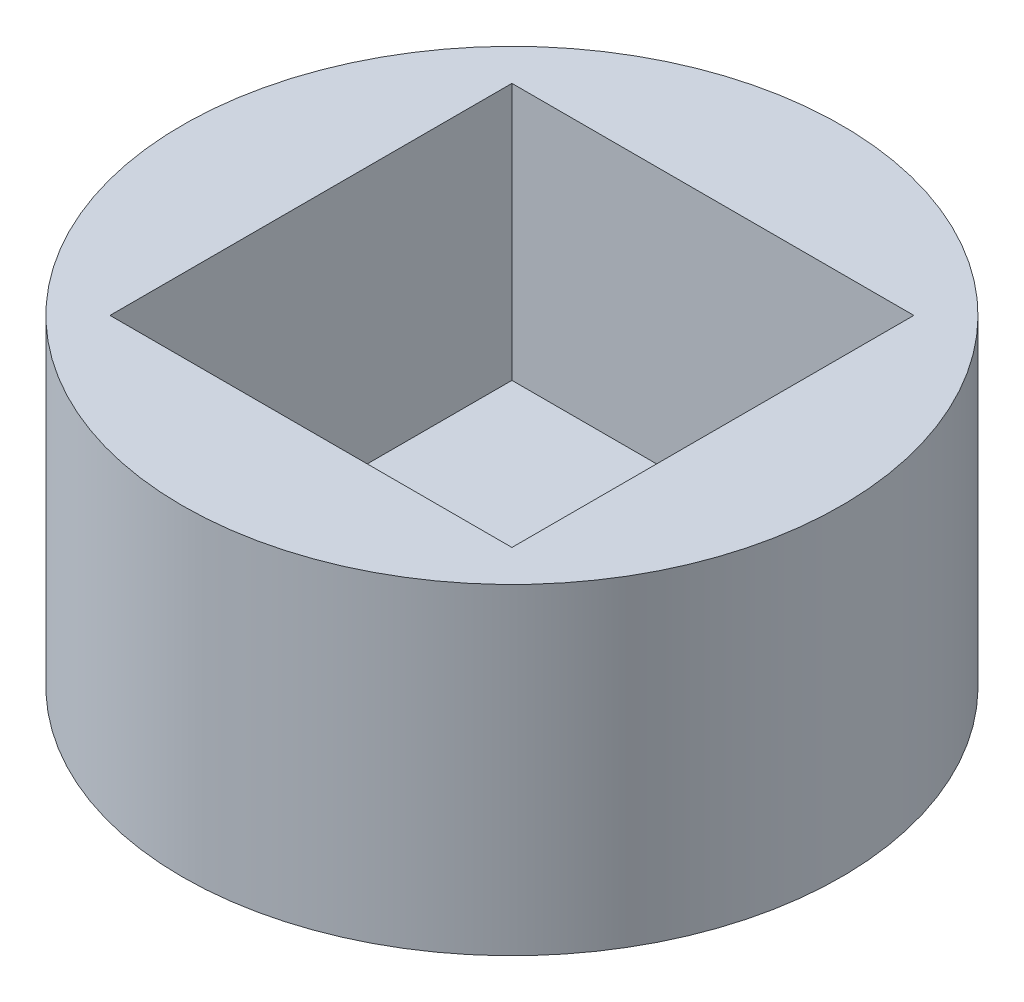
SolidWorks part; units mm, degrees
ref_plane "Front Plane" through (0, 0, 0) normal (0, 0, 1) x (1, 0, 0)
ref_plane "Top Plane" through (0, 0, 0) normal (0, 1, 0) x (1, 0, 0)
ref_plane "Right Plane" through (0, 0, 0) normal (1, 0, 0) x (0, 0, -1)
sketch "Sketch1" plane through (0, 0, 0) normal (0, 1, 0) x (1, 0, 0)
  circle A0 centre (0, 0) radius 26.035
  dimension "D1" = 52.07
extrude "Boss-Extrude1" add sketch "Sketch1" along normal blind 25.4
sketch "Sketch2" plane through (0, 25.4, 0) normal (0, 1, 0) x (1, 0, 0)
  line L1 (-15.875, -15.875) -> (15.875, -15.875)
  line L2 (-15.875, -15.875) -> (-15.875, 15.875)
  line L3 (-15.875, 15.875) -> (15.875, 15.875)
  line L4 (15.875, -15.875) -> (15.875, 15.875)
  line L5 (-15.875, -15.875) -> (15.875, 15.875) construction
  line L6 (-15.875, 15.875) -> (15.875, -15.875) construction
  point P0 (0, 0)
  dimension "D1" = 31.75
  dimension "D2" = 31.75
extrude "Cut-Extrude1" cut sketch "Sketch2" against normal blind 20.32
